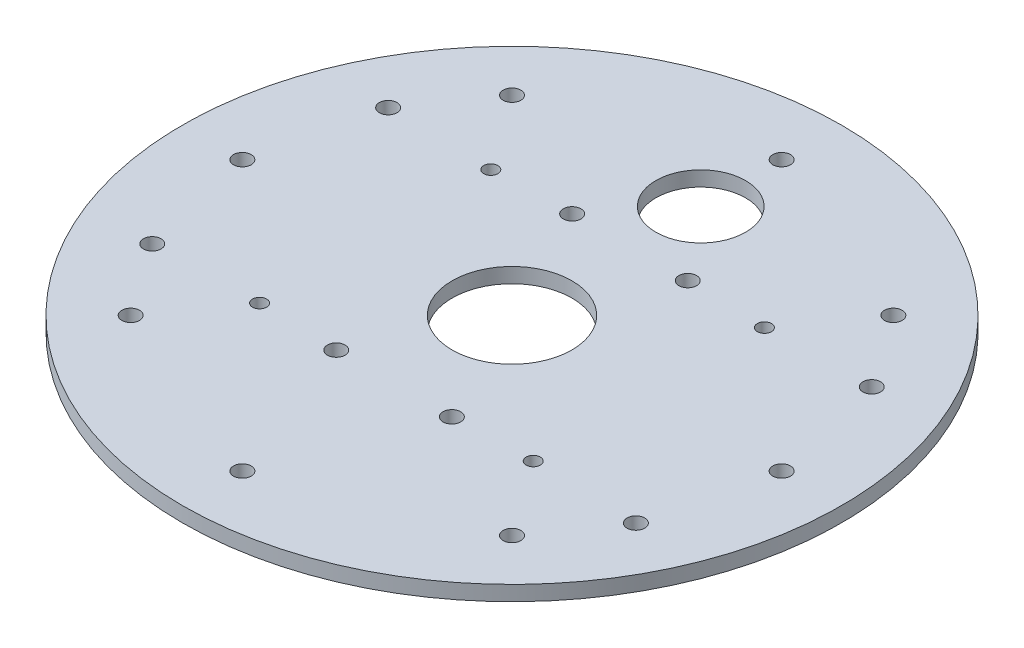
SolidWorks part; units mm, degrees
ref_plane "Front Plane" through (0, 0, 0) normal (0, 0, 1) x (1, 0, 0)
ref_plane "Top Plane" through (0, 0, 0) normal (0, 1, 0) x (1, 0, 0)
ref_plane "Right Plane" through (0, 0, 0) normal (1, 0, 0) x (0, 0, -1)
sketch "Sketch1" plane through (0, 0, 0) normal (0, 1, 0) x (1, 0, 0)
  circle A0 centre (0, 0) radius 69.85
  dimension "D1" = 139.7
extrude "plate" add sketch "Sketch1" along normal blind 3.175 contours A0
sketch "Sketch2" plane through (0, 0, 0) normal (0, -1, 0) x (1, 0, 0)
  circle A0 centre (0, 0) radius 12.7
  dimension "D1" = 25.4
extrude "plate center hole" cut sketch "Sketch2" against normal up to next
sketch "Sketch13" plane through (0, 0, 0) normal (0, -1, 0) x (1, 0, 0)
  line L0 (0, 0) -> (0, 69.85) construction
  line L1 (0, 0) -> (-69.85, 0) construction
  circle A0 centre (0, 0) radius 69.85 construction
  circle A1 centre (-12.25, 25) radius 1.875
  circle A2 centre (-51.25, 25) radius 1.875
  circle A3 centre (-51.25, -25) radius 1.875
  circle A4 centre (-12.25, -25) radius 1.875
  circle A5 centre (12.25, -25) radius 1.875
  circle A6 centre (51.25, -25) radius 1.875
  circle A7 centre (51.25, 25) radius 1.875
  circle A8 centre (12.25, 25) radius 1.875
  circle A9 centre (57.15, 0) radius 1.875
  circle A10 centre (40.4112, 40.4112) radius 1.875
  circle A11 centre (40.4112, -40.4112) radius 1.875
  circle A12 centre (0, -57.15) radius 1.875
  circle A13 centre (-40.4112, -40.4112) radius 1.875
  circle A14 centre (-57.15, 0) radius 1.875
  circle A15 centre (-40.4112, 40.4112) radius 1.875
  circle A16 centre (0, 57.15) radius 1.875
  circle A17 centre (-29, -24.5) radius 1.5
  circle A18 centre (-29, 24.5) radius 1.5
  circle A19 centre (29, 24.5) radius 1.5
  circle A20 centre (29, -24.5) radius 1.5
  circle A21 centre (0, -40) radius 9.5
  point P5 (-34.925, 0)
  point P36 (0, 0)
  point P44 (0, 0)
  point P46 (0, 0)
  point P52 (0, 0)
  point P53 (0, 0)
  dimension "D1" = 3
  dimension "D3" = 3.75
  dimension "D5" = 8
  dimension "D6" = 3.75
  dimension "D10" = 19
  dimension "D11" = 40
  dimension "D2" = 25
  dimension "D4" = 57.15
  dimension "D7" = 12.25
  dimension "D8" = 24.5
  dimension "D9" = 29
extrude "plate through holes" cut sketch "Sketch13" against normal up to next
